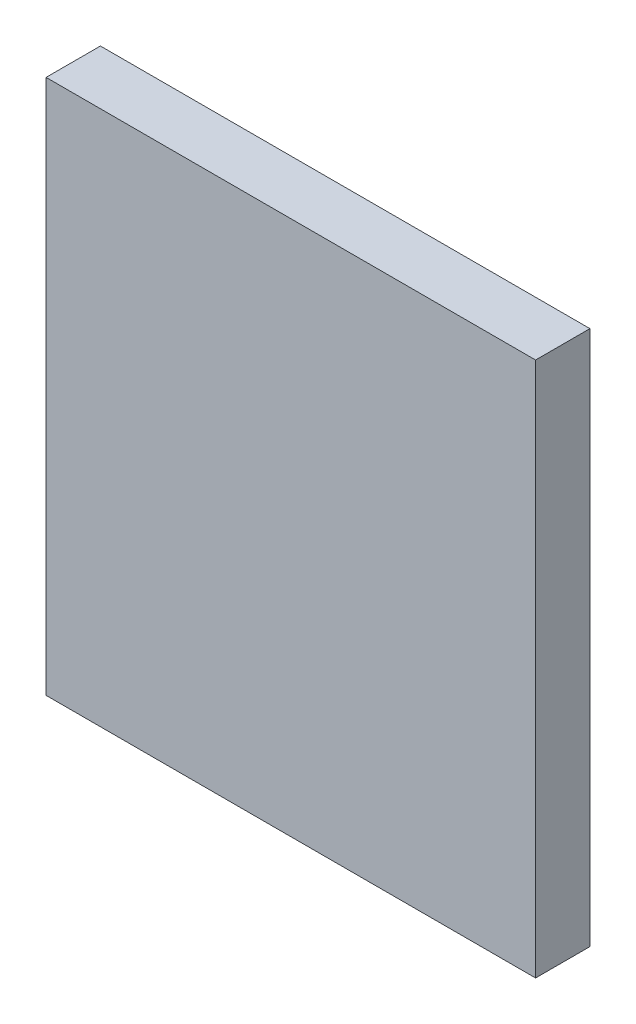
SolidWorks part; units mm, degrees
ref_plane "Ebene vorne" through (0, 0, 0) normal (0, 0, 1) x (1, 0, 0)
ref_plane "Ebene oben" through (0, 0, 0) normal (0, 1, 0) x (1, 0, 0)
ref_plane "Ebene rechts" through (0, 0, 0) normal (1, 0, 0) x (0, 0, -1)
sketch "Skizze1" plane through (0, 0, 0) normal (0, 0, 1) x (1, 0, 0)
  line L0 (-6.4017, 4.9501) -> (2.6072, 4.9501)
  line L1 (2.6072, 4.9501) -> (2.6072, -4.8999)
  line L2 (2.6072, -4.8999) -> (-6.4017, -4.8999)
  line L3 (-6.4017, -4.8999) -> (-6.4017, 4.9501)
extrude "Component_Outline" add sketch "Skizze1" along normal blind 1 separate body
sketch3d "3D-Skizze1"
  line L0 (0, 0, 0) -> (1, 0, 0)
  line L1 (0, 0, 0) -> (0, 1, 0)
  line L2 (0, 0, 0) -> (0, 0, 1)
  point P0 (0, 0, 0)
